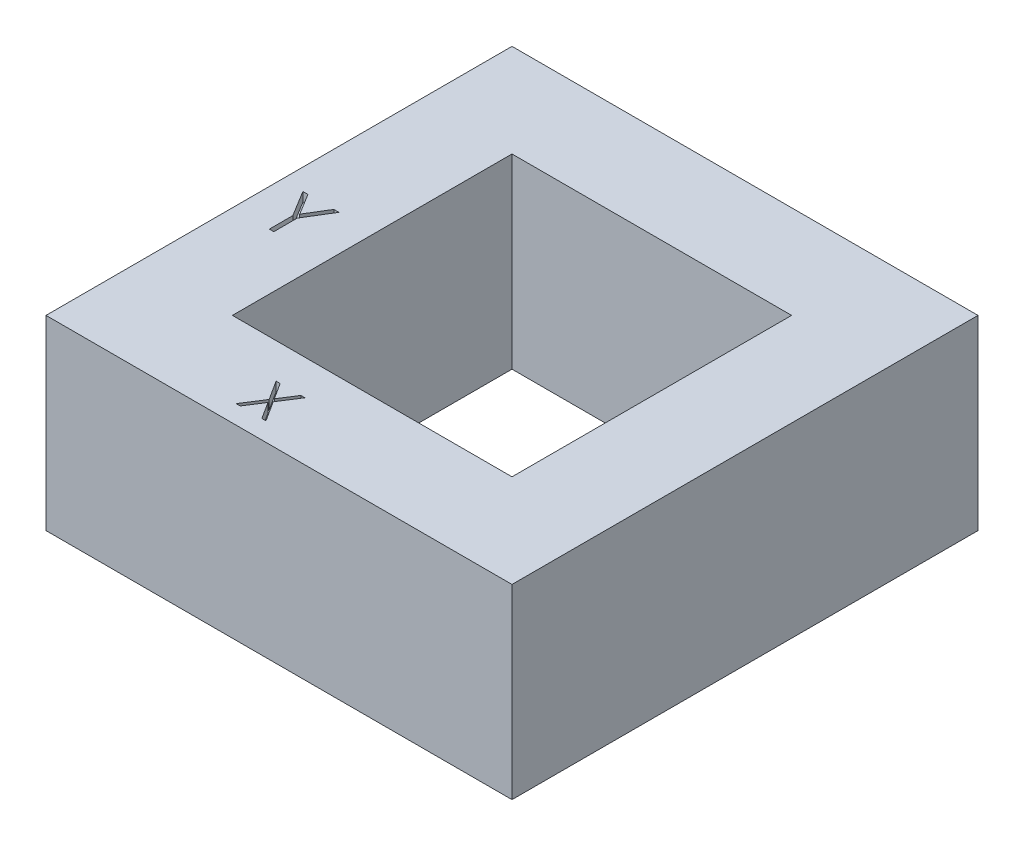
SolidWorks part; units mm, degrees
ref_plane "Front Plane" through (0, 0, 0) normal (0, 0, 1) x (1, 0, 0)
ref_plane "Top Plane" through (0, 0, 0) normal (0, 1, 0) x (1, 0, 0)
ref_plane "Right Plane" through (0, 0, 0) normal (1, 0, 0) x (0, 0, -1)
sketch "Sketch1" plane through (0, 0, 0) normal (0, 1, 0) x (1, 0, 0)
  line L1 (-7.5, -7.5) -> (7.5, -7.5)
  line L2 (-7.5, -7.5) -> (-7.5, 7.5)
  line L3 (-7.5, 7.5) -> (7.5, 7.5)
  line L4 (7.5, -7.5) -> (7.5, 7.5)
  line L5 (-7.5, -7.5) -> (7.5, 7.5) construction
  line L6 (-7.5, 7.5) -> (7.5, -7.5) construction
  line L7 (-12.5, -12.5) -> (12.5, -12.5)
  line L8 (-12.5, -12.5) -> (-12.5, 12.5)
  line L9 (-12.5, 12.5) -> (12.5, 12.5)
  line L10 (12.5, -12.5) -> (12.5, 12.5)
  line L11 (-12.5, -12.5) -> (12.5, 12.5) construction
  line L12 (-12.5, 12.5) -> (12.5, -12.5) construction
  point P0 (0, 0)
  point P6 (0, 0)
  dimension "D1" = 25
  dimension "D2" = 15
extrude "Boss-Extrude1" add sketch "Sketch1" along normal blind 10
sketch "Sketch2" plane through (0, 10, 0) normal (0, 1, 0) x (1, 0, 0)
  line L0 (-12.5, 7.5) -> (-7.5, 7.5) construction
  line L1 (-12.5, 12.5) -> (-12.5, -12.5) construction
  line L2 (-7.5, 7.5) -> (-7.5, -7.5) construction
  line L3 (7.5, -7.5) -> (7.5, -12.5) construction
  line L4 (-7.5, -7.5) -> (7.5, -7.5) construction
  line L5 (-12.5, -12.5) -> (12.5, -12.5) construction
  line L6 (7.5, -11.5) -> (-12.5, -11.5) construction
  line L7 (-11.5, 7.5) -> (-11.5, -12.5) construction
  line L8 (-11.5, -2.5) -> (-9.4062, -2.5) construction
  text T0 "X" font "Century Gothic" height in points 8
  text T1 "Y" font "Century Gothic" height in points 10
  dimension "D1" = 1
  dimension "D3" = 1
extrude "Cut-Extrude1" cut sketch "Sketch2" against normal blind 0.5
